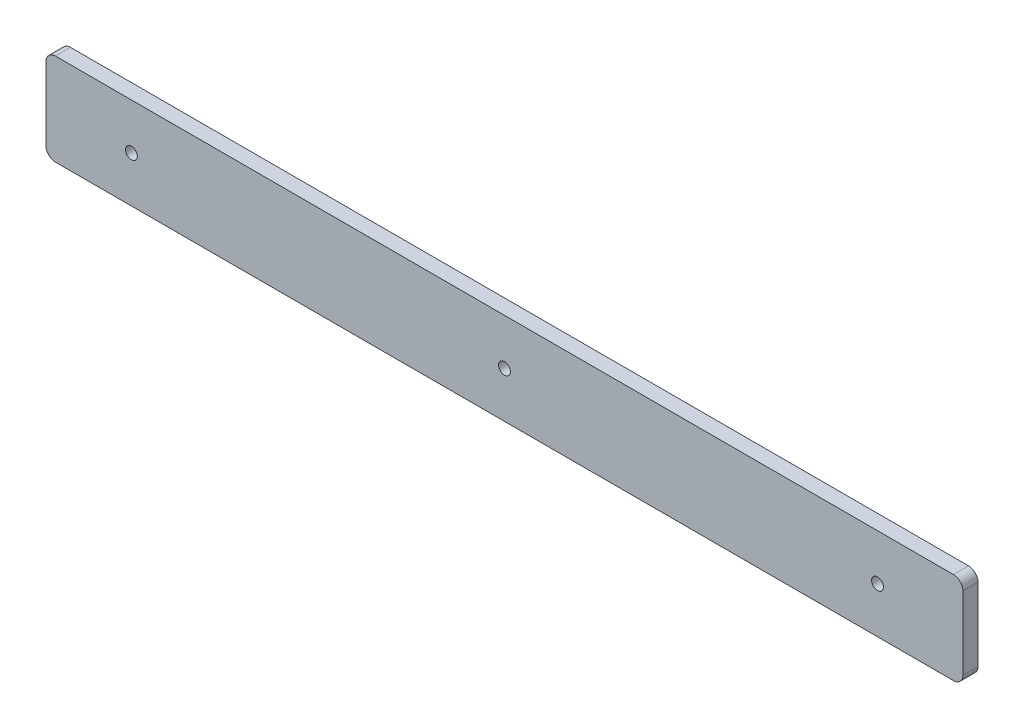
SolidWorks part; units mm, degrees
material "1100-H12 Rod (SS)"
ref_plane "X-Y Datum" through (0, 0, 0) normal (0, 0, 1) x (1, 0, 0)
ref_plane "X-Z Datum" through (0, 0, 0) normal (0, 1, 0) x (1, 0, 0)
ref_plane "Y-Z Datum" through (0, 0, 0) normal (1, 0, 0) x (0, 0, -1)
sketch "Sketch1" plane through (0, 0, 0) normal (0, 0, 1) x (1, 0, 0)
  line L1 (0, 0) -> (97.398, 0)
  line L2 (0, 0) -> (0, 9.7577)
  line L3 (0, 9.7577) -> (97.398, 9.7577)
  line L4 (97.398, 0) -> (97.398, 9.7577)
extrude "Boss-Extrude1" add sketch "Sketch1" along normal blind 1.6002 contours L3 L4 L1 L2
sketch "Sketch2" plane through (0, 0, 1.6002) normal (0, 0, 1) x (1, 0, 0)
  line L0 (0, 4.8788) -> (9.075, 4.8788) construction
  line L1 (0, 0) -> (0, 9.7577) construction
  line L2 (9.075, 4.8788) -> (48.699, 4.8788) construction
  line L3 (97.398, 4.8788) -> (88.323, 4.8788) construction
  line L4 (97.398, 0) -> (97.398, 9.7577) construction
  circle A0 centre (9.075, 4.8788) radius 0.625
  circle A1 centre (48.699, 4.8788) radius 0.625
  circle A2 centre (88.323, 4.8788) radius 0.625
extrude "Cut-Extrude1" cut sketch "Sketch2" against normal through all
fillet "Fillet1" radius 1 4 edges at (97.398, 0, 0.8001) (97.398, 9.7577, 0.8001) (0, 0, 0.8001) (0, 9.7577, 0.8001)
